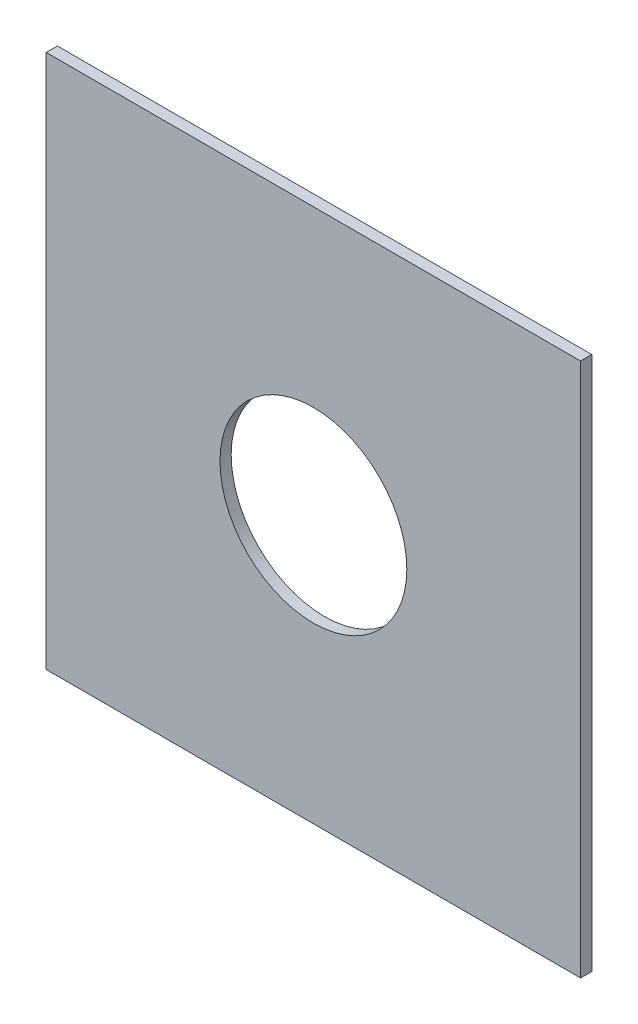
SolidWorks part; units mm, degrees
ref_plane "Front Plane" through (0, 0, 0) normal (0, 0, 1) x (1, 0, 0)
ref_plane "Top Plane" through (0, 0, 0) normal (0, 1, 0) x (1, 0, 0)
ref_plane "Right Plane" through (0, 0, 0) normal (1, 0, 0) x (0, 0, -1)
sketch "Sketch1" plane through (0, 0, 0) normal (0, 0, 1) x (1, 0, 0)
  line L1 (-71.5, -71.5) -> (71.5, -71.5)
  line L2 (-71.5, -71.5) -> (-71.5, 71.5)
  line L3 (-71.5, 71.5) -> (71.5, 71.5)
  line L4 (71.5, -71.5) -> (71.5, 71.5)
  line L5 (-71.5, -71.5) -> (71.5, 71.5) construction
  line L6 (-71.5, 71.5) -> (71.5, -71.5) construction
  circle A0 centre (0, 0) radius 25
  point P0 (0, 0)
extrude "Boss-Extrude1" add sketch "Sketch1" along normal blind 3
